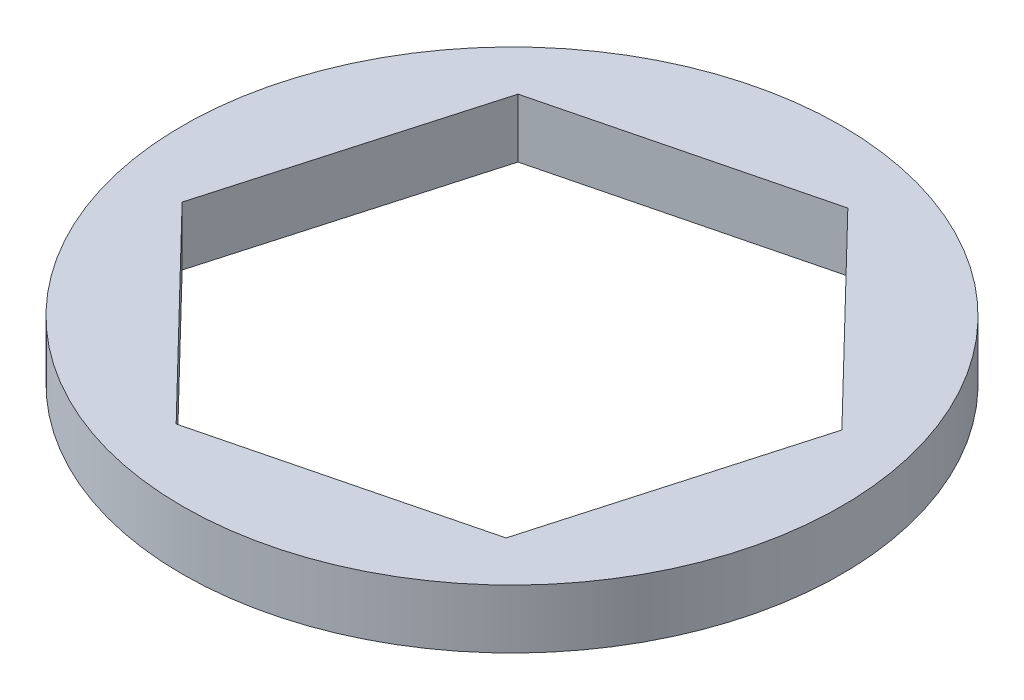
SolidWorks part; units mm, degrees
ref_plane "Front Plane" through (0, 0, 0) normal (0, 0, 1) x (1, 0, 0)
ref_plane "Top Plane" through (0, 0, 0) normal (0, 1, 0) x (1, 0, 0)
ref_plane "Right Plane" through (0, 0, 0) normal (1, 0, 0) x (0, 0, -1)
sketch "Sketch1" plane through (0, 0, 0) normal (0, 1, 0) x (1, 0, 0)
  line L1 (2.0076, 7.0522) -> (-5.1036, 5.2647)
  line L2 (-5.1036, 5.2647) -> (-7.1111, -1.7875)
  line L3 (-7.1111, -1.7875) -> (-2.0076, -7.0522)
  line L4 (-2.0076, -7.0522) -> (5.1036, -5.2647)
  line L5 (5.1036, -5.2647) -> (7.1111, 1.7875)
  line L6 (7.1111, 1.7875) -> (2.0076, 7.0522)
  circle A0 centre (0, 0) radius 6.35 construction
  circle A1 centre (0, 0) radius 8.89
  dimension "D2" = 17.78
  dimension "D1" = 12.7
extrude "Boss-Extrude1" add sketch "Sketch1" along normal blind 1.5875
